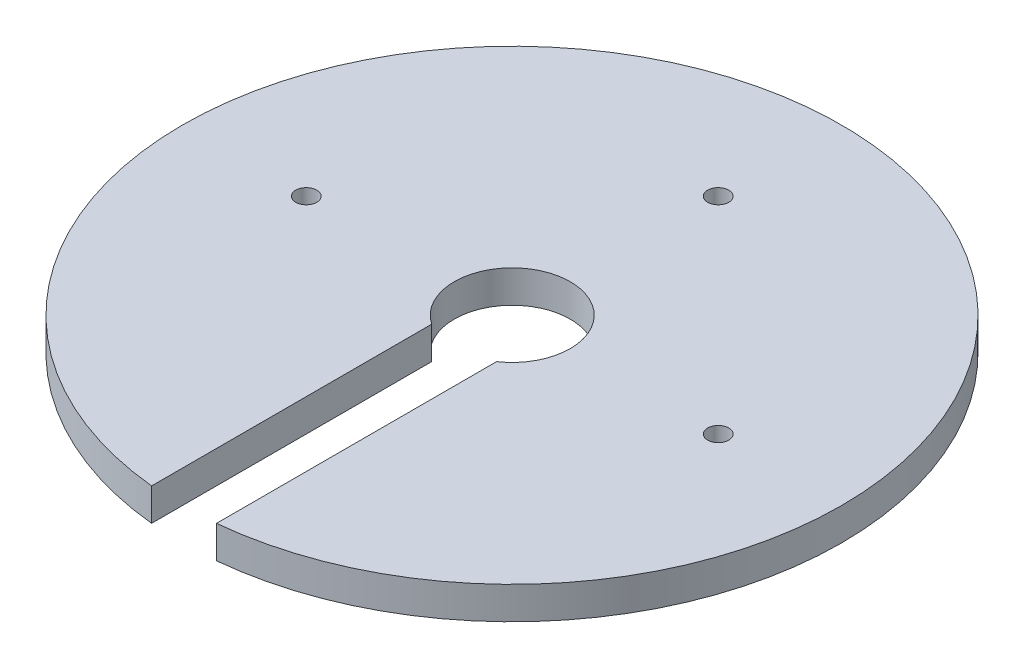
SolidWorks part; units mm, degrees
ref_plane "Front Plane" through (0, 0, 0) normal (0, 0, 1) x (1, 0, 0)
ref_plane "Top Plane" through (0, 0, 0) normal (0, 1, 0) x (1, 0, 0)
ref_plane "Right Plane" through (0, 0, 0) normal (1, 0, 0) x (0, 0, -1)
sketch "Sketch1" plane through (0, 0, 0) normal (0, 1, 0) x (1, 0, 0)
  circle A0 centre (0, 0) radius 101.6
  dimension "D1" = 203.2
extrude "Boss-Extrude1" add sketch "Sketch1" along normal blind 10
sketch "Sketch2" plane through (0, 10, 0) normal (0, 1, 0) x (1, 0, 0)
  line L1 (10, -14.7467) -> (10, -101.1067)
  line L2 (-10, -14.7467) -> (-10, -101.1067)
  circle A0 centre (0, 0) radius 101.6 construction
  arc A1 (-10, -14.7467) -> (10, -14.7467) centre (0, 0.0708) cw
  arc A2 (-10, -101.1067) -> (10, -101.1067) centre (0, 0) ccw
  circle A3 centre (63.5, 0.0708) radius 3.25
  circle A4 centre (-63.5, 0.0708) radius 3.25
  circle A5 centre (0, 63.5708) radius 3.25
  dimension "D4" = 6.5
  dimension "D1" = 20
  dimension "D2" = 10
  dimension "D3" = 86.36
  dimension "D5" = 63.5
  dimension "D6" = 63.5
  dimension "D7" = 63.5
extrude "Cut-Extrude1" cut sketch "Sketch2" against normal through all
